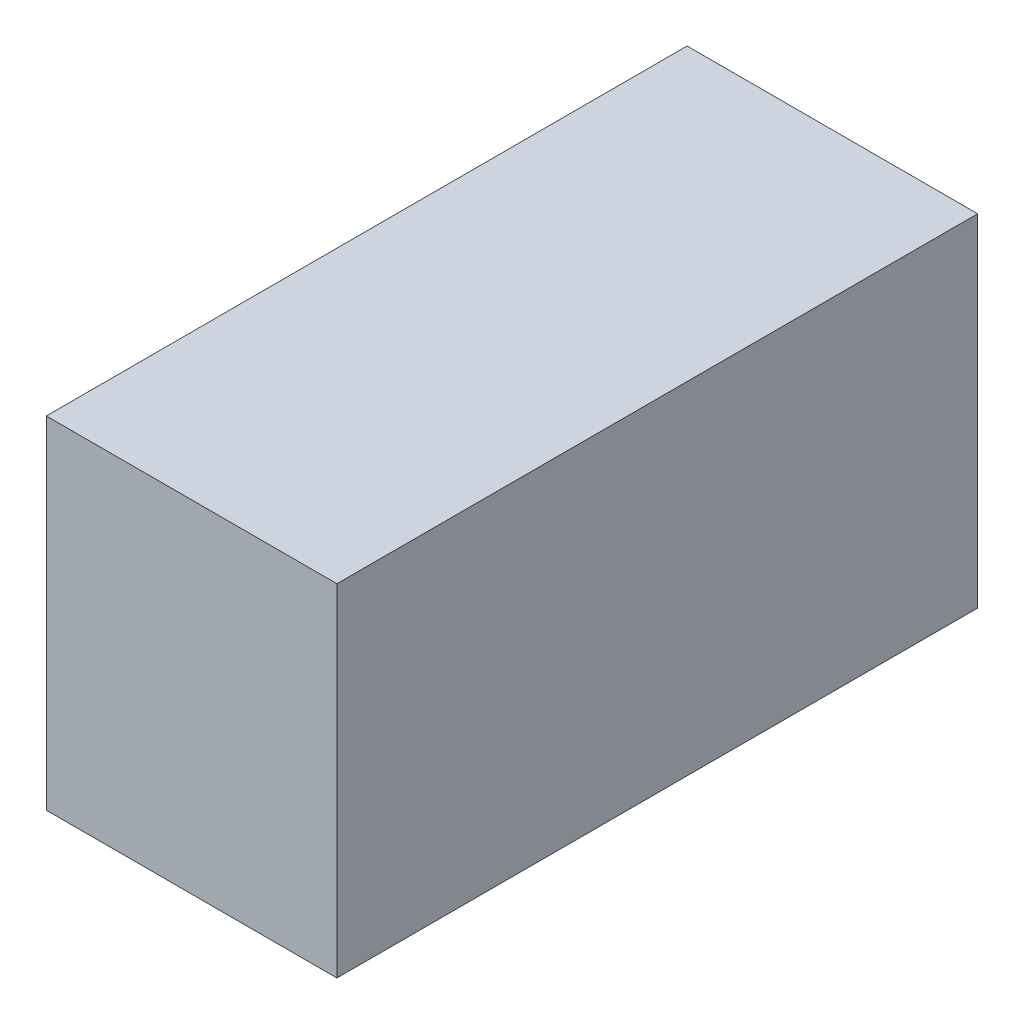
SolidWorks part; units mm, degrees
ref_plane "Front Plane" through (0, 0, 0) normal (0, 0, 1) x (1, 0, 0)
ref_plane "Top Plane" through (0, 0, 0) normal (0, 1, 0) x (1, 0, 0)
ref_plane "Right Plane" through (0, 0, 0) normal (1, 0, 0) x (0, 0, -1)
sketch "Sketch1" plane through (0, 0, 0) normal (0, 0, 1) x (1, 0, 0)
  line L1 (-10, -11.75) -> (10, -11.75)
  line L2 (-10, -11.75) -> (-10, 11.75)
  line L3 (-10, 11.75) -> (10, 11.75)
  line L4 (10, -11.75) -> (10, 11.75)
  line L5 (-10, -11.75) -> (10, 11.75) construction
  line L6 (-10, 11.75) -> (10, -11.75) construction
  point P0 (0, 0)
extrude "Envelope" add sketch "Sketch1" along normal blind 44.1
